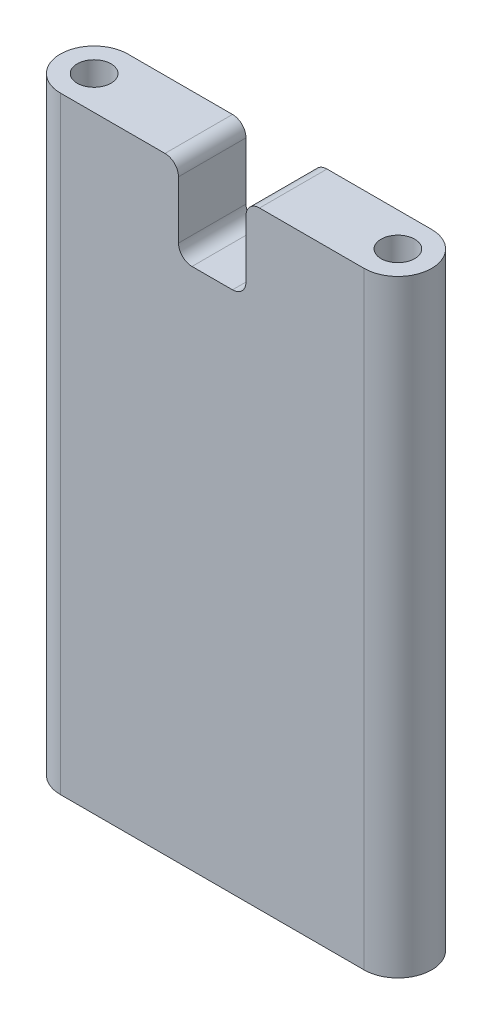
SolidWorks part; units mm, degrees
ref_plane "前视基准面" through (0, 0, 0) normal (0, 0, 1) x (1, 0, 0)
ref_plane "上视基准面" through (0, 0, 0) normal (0, 1, 0) x (1, 0, 0)
ref_plane "右视基准面" through (0, 0, 0) normal (1, 0, 0) x (0, 0, -1)
other "Configuration Table"
sketch "Sketch2" plane through (0, 0, 0) normal (0, 1, 0) x (1, 0, 0)
  line L0 (0, 0) -> (28.575, 0) construction
  line L2 (-28.575, 6.35) -> (28.575, 6.35)
  line L3 (28.575, -6.35) -> (-28.575, -6.35)
  circle A0 centre (28.575, 0) radius 3.175
  arc A1 (28.575, -6.35) -> (28.575, 6.35) centre (28.575, 0) ccw
  circle A2 centre (-28.575, 0) radius 3.175
  arc A3 (-28.575, 6.35) -> (-28.575, -6.35) centre (-28.575, 0) ccw
  dimension "D3" = 6.35
  dimension "D4" = 12.7
  dimension "D5" = 6.35
  dimension "D6" = 12.7
  dimension "D1" = 57.15
  dimension "D2" = 57.15
  dimension "D7" = 12.7
  dimension "D8" = 28.575
extrude "Boss-Extrude1" add sketch "Sketch2" along normal mid plane 114.3
sketch "Sketch7" plane through (0, 0, 6.35) normal (0, 0, 1) x (1, 0, 0)
  line L0 (-6.35, 57.15) -> (-6.35, 41.275)
  line L1 (-28.575, 57.15) -> (28.575, 57.15) construction
  line L2 (-6.35, 41.275) -> (6.35, 41.275)
  line L3 (6.35, 41.275) -> (6.35, 57.15)
  line L4 (6.35, 57.15) -> (-6.35, 57.15)
  line L5 (0, -6.985) -> (0, 6.985) construction
  dimension "D1" = 6.35
  dimension "D2" = 6.35
  dimension "D3" = 15.875
extrude "Cut-Extrude3" cut sketch "Sketch7" against normal through all
fillet "Fillet1" radius 2.54 4 edges at (6.35, 41.275, 0) (6.35, 57.15, 0) (-6.35, 41.275, 0) (-6.35, 57.15, 0)
equation "\"D2@Sketch7\"=\"D1@Sketch7\""
